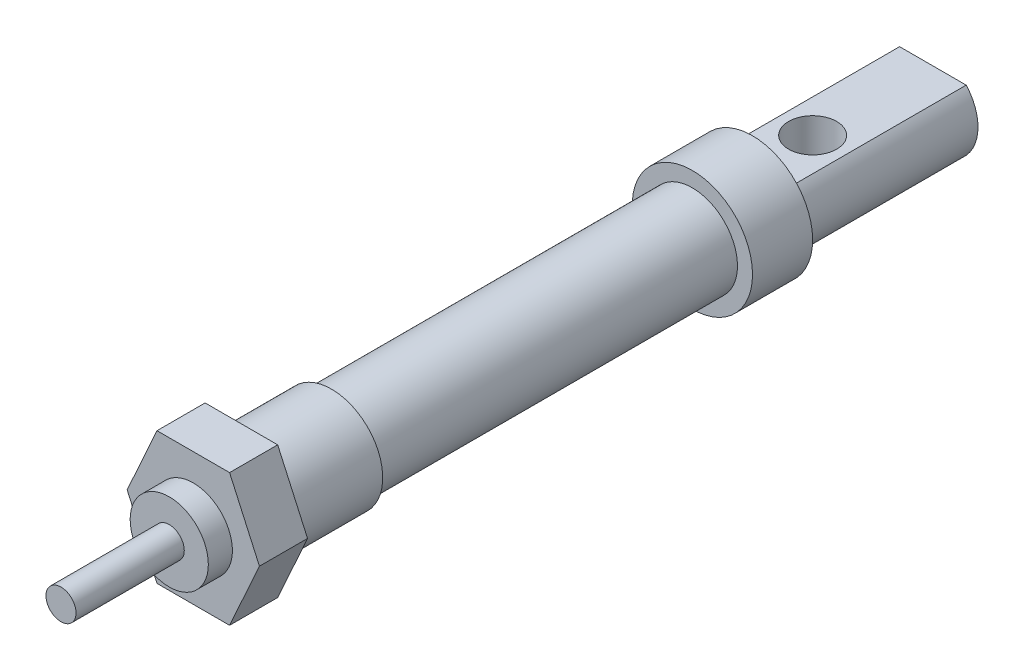
SolidWorks part; units mm, degrees
ref_plane "Front Plane" through (0, 0, 0) normal (0, 0, 1) x (1, 0, 0)
ref_plane "Top Plane" through (0, 0, 0) normal (0, 1, 0) x (1, 0, 0)
ref_plane "Right Plane" through (0, 0, 0) normal (1, 0, 0) x (0, 0, -1)
sketch "Sketch1" plane through (0, 0, 0) normal (0, 0, 1) x (1, 0, 0)
  circle A0 centre (0, 0) radius 9.525
  dimension "D1" = 19.05
extrude "Boss-Extrude1" add sketch "Sketch1" along normal blind 38.1 contours A0
sketch "Sketch2" plane through (0, 0, 38.1) normal (0, 0, 1) x (1, 0, 0)
  circle A0 centre (0, 0) radius 12.7
  dimension "D1" = 25.4
extrude "Boss-Extrude2" add sketch "Sketch2" along normal blind 12.7 contours A0
sketch "Sketch3" plane through (0, 0, 50.8) normal (0, 0, 1) x (1, 0, 0)
  circle A0 centre (0, 0) radius 9.525
  dimension "D1" = 19.05
extrude "Boss-Extrude3" add sketch "Sketch3" along normal blind 76.2
sketch "Sketch4" plane through (0, 0, 127) normal (0, 0, 1) x (1, 0, 0)
  circle A0 centre (0, 0) radius 10.795
  dimension "D1" = 21.59
extrude "Boss-Extrude4" add sketch "Sketch4" along normal blind 19.05 contours A0
sketch "Sketch5" plane through (0, 0, 146.05) normal (0, 0, 1) x (1, 0, 0)
  line L0 (-7.6637, 13.97) -> (7.6637, 13.97)
  line L1 (7.6637, 13.97) -> (13.97, 0)
  line L2 (13.97, 0) -> (7.6637, -13.97)
  line L3 (7.6637, -13.97) -> (-7.6637, -13.97)
  line L4 (-7.6637, -13.97) -> (-13.97, 0)
  line L5 (-13.97, 0) -> (-7.6637, 13.97)
  line L6 (-13.97, 0) -> (13.97, 0) construction
  line L7 (0, 13.97) -> (0, -13.97) construction
  point P7 (0, 13.97)
  point P10 (0, 0)
  point P14 (0, -13.97)
  dimension "D1" = 27.94
extrude "Boss-Extrude5" add sketch "Sketch5" along normal blind 10.16 contours L1 L2 L3 L4 L5 L0
sketch "Sketch6" plane through (0, 0, 156.21) normal (0, 0, 1) x (1, 0, 0)
  circle A0 centre (0, 0) radius 8.255
  dimension "D1" = 16.51
extrude "Boss-Extrude6" add sketch "Sketch6" along normal blind 5.08 contours A0
sketch "Sketch7" plane through (0, 0, 161.29) normal (0, 0, 1) x (1, 0, 0)
  circle A0 centre (0, 0) radius 3.175
  dimension "D1" = 6.35
extrude "Boss-Extrude7" add sketch "Sketch7" along normal blind 22.86 contours A0
sketch "Sketch8" plane through (0, 0, 0) normal (0, 1, 0) x (1, 0, 0)
  line L0 (12.7, -38.1) -> (-12.7, -38.1) construction
  circle A0 centre (0, -25.4) radius 5.08
  point P4 (-12.5048, -25.4)
  point P5 (0, 0)
  dimension "D1" = 10.16
  dimension "D2" = 12.7
extrude "Cut-Extrude1" cut sketch "Sketch8" against normal blind 22.86 and the other way blind 22.86
sketch "Sketch9" plane through (0, 0, 0) normal (0, 0, -1) x (-1, 0, 0)
  line L1 (-7.0335, 6.4231) -> (9.0536, 6.4231)
  line L2 (-7.0335, 6.4231) -> (-7.0335, 12.3669)
  line L3 (-7.0335, 12.3669) -> (9.0536, 12.3669)
  line L4 (9.0536, 6.4231) -> (9.0536, 12.3669)
  circle A1 centre (0, 0) radius 9.525 construction
extrude "Cut-Extrude2" cut sketch "Sketch9" against normal blind 38.1
mirror "Mirror1" about plane through (0, 0, 0) normal (0, 1, 0) of "Cut-Extrude2"
